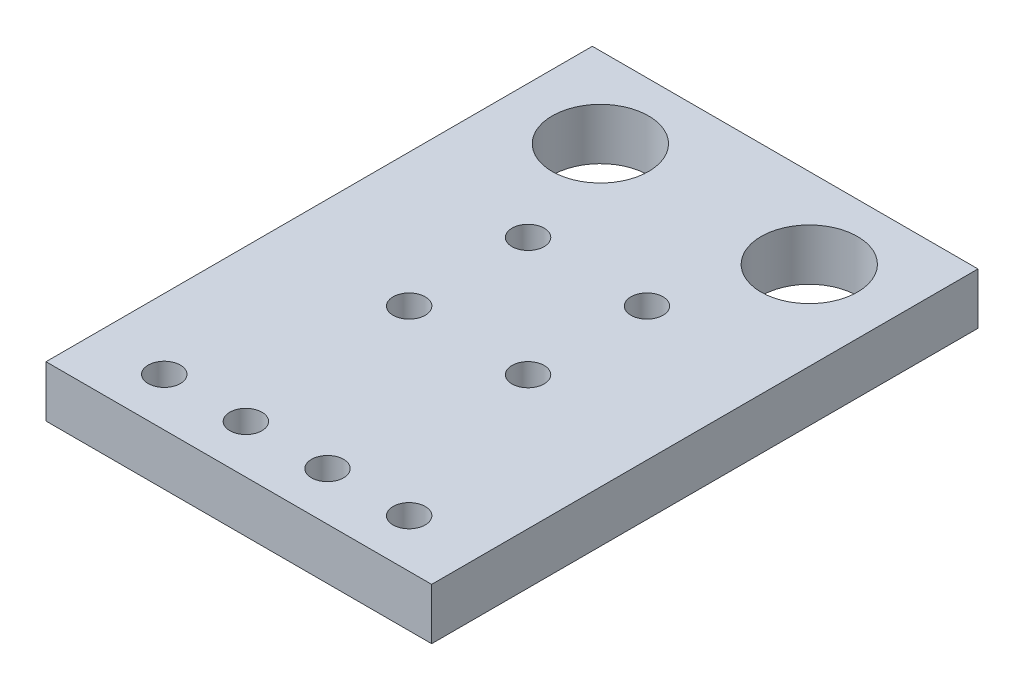
SolidWorks part; units mm, degrees
ref_plane "Спереди" through (0, 0, 0) normal (0, 0, 1) x (1, 0, 0)
ref_plane "Сверху" through (0, 0, 0) normal (0, 1, 0) x (1, 0, 0)
ref_plane "Справа" through (0, 0, 0) normal (1, 0, 0) x (0, 0, -1)
sketch "Эскиз2" plane through (0, 0, 0) normal (0, 1, 0) x (1, 0, 0)
  line L0 (-3.25, -2.5) -> (3.25, -2.5) construction
  line L1 (-6, 0) -> (6, 0)
  line L2 (-6, 0) -> (-6, -17)
  line L3 (-6, -17) -> (6, -17)
  line L4 (6, 0) -> (6, -17)
  line L5 (-3.25, 2.0633) -> (-3.25, -49997.9367) construction
  line L6 (3.25, 9.2204) -> (3.25, -49990.7796) construction
  line L7 (-5.7644, -15.5) -> (49994.2356, -15.5) construction
  line L8 (0, -17) -> (0, 49983) construction
  line L9 (-9.2527, -8) -> (49990.7473, -8) construction
  line L10 (-8.4806, -6.15) -> (49991.5194, -6.15) construction
  line L11 (-8.7214, -9.85) -> (49991.2786, -9.85) construction
  line L12 (1.85, -4.5908) -> (1.85, -50004.5908) construction
  line L13 (-1.85, -3.9372) -> (-1.85, -50003.9372) construction
  circle A0 centre (-3.25, -2.5) radius 1.5
  circle A1 centre (3.25, -2.5) radius 1.5
  circle A2 centre (-3.82, -15.5) radius 0.5
  circle A3 centre (-1.28, -15.5) radius 0.5
  circle A4 centre (1.26, -15.5) radius 0.5
  circle A5 centre (3.8, -15.5) radius 0.5
  circle A7 centre (-1.85, -6.15) radius 0.5
  circle A8 centre (-1.85, -9.85) radius 0.5
  circle A9 centre (1.85, -9.85) radius 0.5
  circle A10 centre (1.85, -6.15) radius 0.5
  point P4 (0, -2.5)
  point P26 (0, -17)
  point P47 (0, 0)
  dimension "D6" = 3
  dimension "D7" = 3
  dimension "D8" = 1
  dimension "D9" = 1
  dimension "D10" = 1
  dimension "D11" = 1
  dimension "D12" = 2.54
  dimension "D13" = 2.54
  dimension "D14" = 2.54
  dimension "D15" = 2.2
  dimension "D16" = 9
  dimension "D25" = 1
  dimension "D1" = 12
  dimension "D2" = 17
  dimension "D3" = 2.5
  dimension "D4" = 6.5
  dimension "D5" = 1.5
  dimension "D18" = 1.85
  dimension "D19" = 1.85
  dimension "D20" = 1.85
  dimension "D21" = 1.85
extrude "Бобышка-Вытянуть1" add sketch "Эскиз2" along normal blind 1.6
